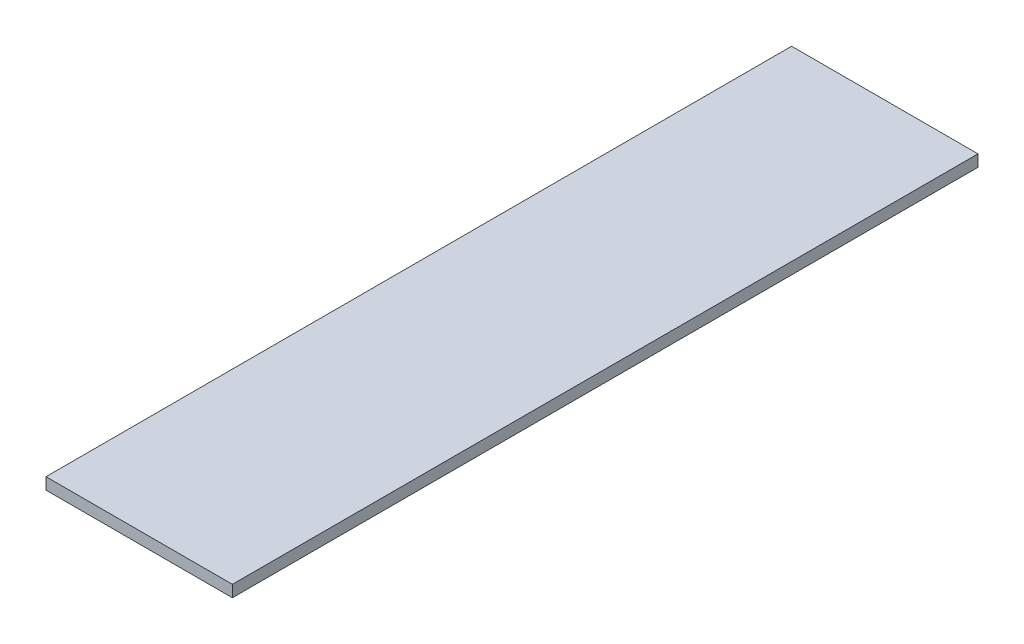
SolidWorks part; units mm, degrees
ref_plane "Front" through (0, 0, 0) normal (0, 0, 1) x (1, 0, 0)
ref_plane "Top" through (0, 0, 0) normal (0, 1, 0) x (1, 0, 0)
ref_plane "Right" through (0, 0, 0) normal (1, 0, 0) x (0, 0, -1)
sketch "Sketch1" plane through (0, 0, 0) normal (0, 1, 0) x (1, 0, 0)
  line L1 (0, 0) -> (50.8, 0)
  line L2 (0, 0) -> (0, 203.2)
  line L3 (0, 203.2) -> (50.8, 203.2)
  line L4 (50.8, 0) -> (50.8, 203.2)
  dimension "D1" = 50.8
  dimension "D2" = 203.2
extrude "Boss-Extrude1" add sketch "Sketch1" along normal blind 3.175
sketch "Sketch2" plane through (0, 3.175, 0) normal (0, 1, 0) x (1, 0, 0)
  line L0 (20.7066, 0) -> (0, 112.0901)
  line L1 (0, 0) -> (50.8, 0) construction
  line L2 (0, 203.2) -> (0, 0) construction
  line L3 (0, 112.0901) -> (0, 0)
  line L4 (0, 0) -> (20.7066, 0)
